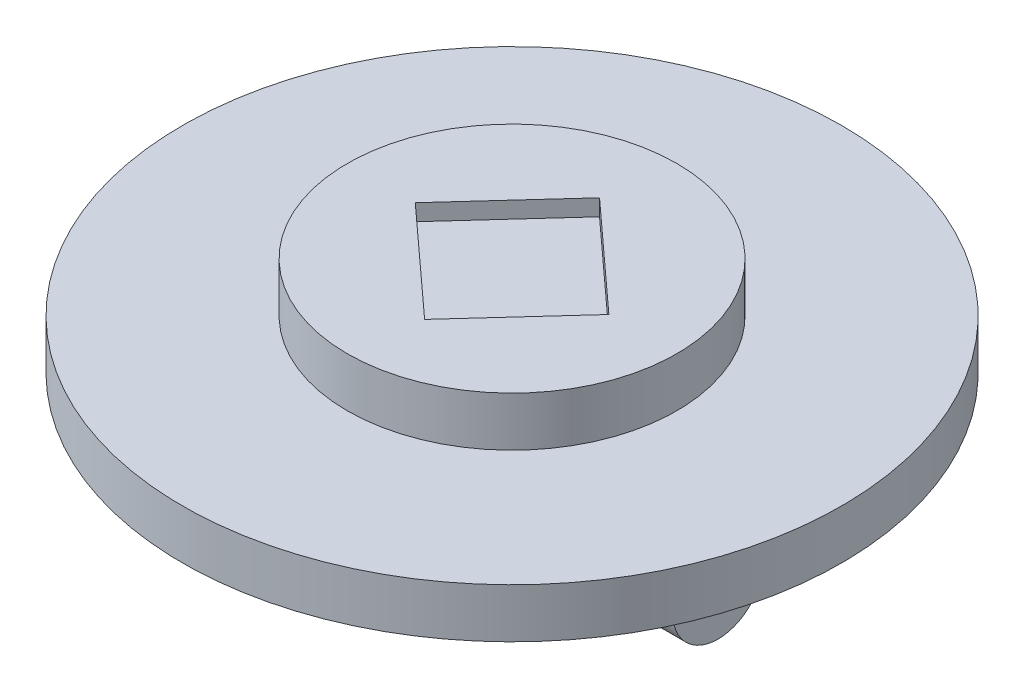
SolidWorks part; units mm, degrees
ref_plane "Front Plane" through (0, 0, 0) normal (0, 0, 1) x (1, 0, 0)
ref_plane "Top Plane" through (0, 0, 0) normal (0, 1, 0) x (1, 0, 0)
ref_plane "Right Plane" through (0, 0, 0) normal (1, 0, 0) x (0, 0, -1)
sketch "Sketch1" plane through (0, 0, 0) normal (0, 1, 0) x (1, 0, 0)
  circle A0 centre (0, 0) radius 50.8
  dimension "D1" = 101.6
extrude "Boss-Extrude1" add sketch "Sketch1" along normal blind 7.62
sketch "Sketch2" plane through (0, 0, 0) normal (0, -1, 0) x (1, 0, 0)
  line L1 (-31.75, -6.985) -> (-26.67, -6.985)
  line L2 (-31.75, -6.985) -> (-31.75, 6.985)
  line L3 (-31.75, 6.985) -> (-26.67, 6.985)
  line L4 (-26.67, -6.985) -> (-26.67, 6.985)
  line L5 (-31.75, -6.985) -> (-26.67, 6.985) construction
  line L6 (-31.75, 6.985) -> (-26.67, -6.985) construction
  point P0 (-29.21, 0)
  dimension "D1" = 29.21
  dimension "D2" = 5.08
  dimension "D3" = 13.97
extrude "Boss-Extrude2" add sketch "Sketch2" along normal blind 12.7
sketch "Sketch3" plane through (-31.75, 0, 0) normal (-1, 0, 0) x (0, 0, 1)
  line L0 (6.985, -12.7) -> (-6.985, -12.7) construction
  circle A0 centre (0, -12.7) radius 6.985
extrude "Boss-Extrude3" add sketch "Sketch3" against normal blind 5.08
sketch "Sketch4" plane through (-31.75, 0, 0) normal (-1, 0, 0) x (0, 0, 1)
  circle A0 centre (0, -12.7) radius 2.5161
  dimension "D1" = 5.0322
extrude "Cut-Extrude1" cut sketch "Sketch4" against normal blind 5.08
sketch "Sketch5" plane through (0, 0, 0) normal (0, -1, 0) x (1, 0, 0)
  line L1 (26.67, -6.985) -> (31.75, -6.985)
  line L2 (26.67, -6.985) -> (26.67, 6.985)
  line L3 (26.67, 6.985) -> (31.75, 6.985)
  line L4 (31.75, -6.985) -> (31.75, 6.985)
  line L5 (26.67, -6.985) -> (31.75, 6.985) construction
  line L6 (26.67, 6.985) -> (31.75, -6.985) construction
  point P0 (29.21, 0)
  dimension "D1" = 29.21
  dimension "D2" = 13.97
  dimension "D3" = 5.08
extrude "Boss-Extrude4" add sketch "Sketch5" along normal blind 12.7
sketch "Sketch6" plane through (31.75, 0, 0) normal (1, 0, 0) x (0, 0, -1)
  line L0 (6.985, -12.7) -> (-6.985, -12.7) construction
  circle A0 centre (0, -12.7) radius 6.985
  dimension "D1" = 13.97
extrude "Boss-Extrude5" add sketch "Sketch6" against normal blind 5.08
sketch "Sketch8" plane through (31.75, 0, 0) normal (1, 0, 0) x (0, 0, -1)
  line L0 (6.985, 0) -> (-6.985, 0) construction
  circle A0 centre (0, -12.7) radius 2.54
  point P2 (0, 0)
  dimension "D2" = 5.08
  dimension "D1" = 12.7
extrude "Cut-Extrude2" cut sketch "Sketch8" against normal blind 5.08
sketch "Sketch9" plane through (0, 7.62, 0) normal (0, 1, 0) x (1, 0, 0)
  circle A0 centre (0, 0) radius 25.4
  dimension "D1" = 50.8
extrude "Boss-Extrude6" add sketch "Sketch9" along normal blind 7.62
sketch "Sketch10" plane through (0, 15.24, 0) normal (0, 1, 0) x (1, 0, 0)
  line L0 (1.3787, -14.8587) -> (-14.9225, 0)
  line L1 (1.3787, -14.8587) -> (14.9225, 0)
  line L2 (-14.9225, 0) -> (-1.3787, 14.8587)
  line L3 (14.9225, 0) -> (-1.3787, 14.8587)
  line L4 (1.3787, -14.8587) -> (-1.3787, 14.8587) construction
  line L5 (-14.9225, 0) -> (14.9225, 0) construction
  point P1 (0, 0)
  dimension "D1" = 29.845
  dimension "D2" = 29.845
extrude "Cut-Extrude3" cut sketch "Sketch10" against normal blind 2.54
